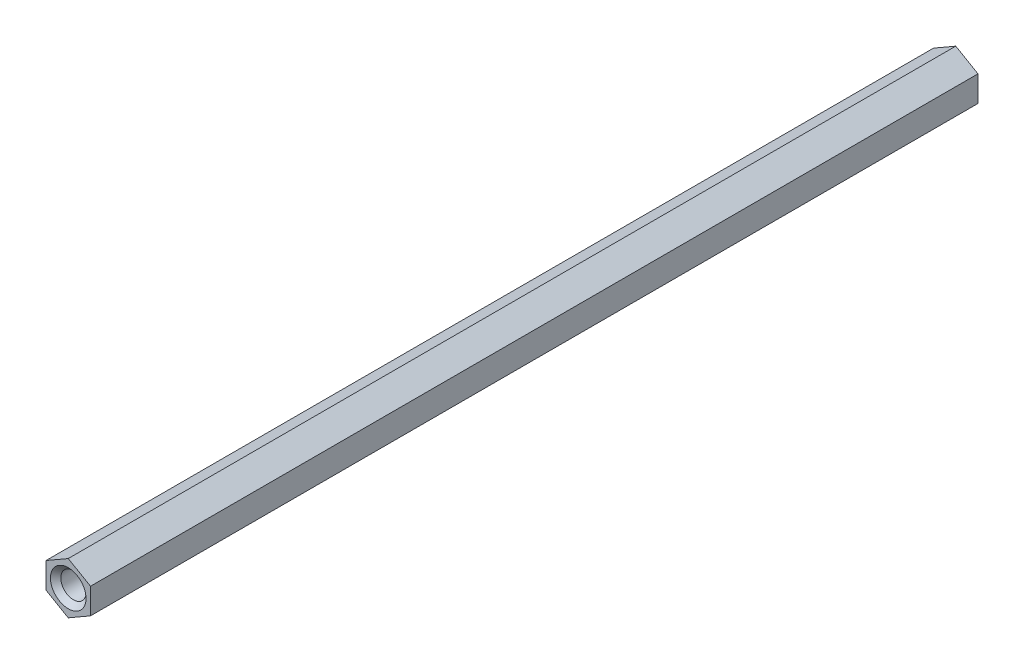
SolidWorks part; units mm, degrees
ref_plane "Front Plane" through (0, 0, 0) normal (0, 0, 1) x (1, 0, 0)
ref_plane "Top Plane" through (0, 0, 0) normal (0, 1, 0) x (1, 0, 0)
ref_plane "Right Plane" through (0, 0, 0) normal (1, 0, 0) x (0, 0, -1)
sketch "Sketch1" plane through (0, 0, 0) normal (0, 0, 1) x (1, 0, 0)
  line L0 (-4.7625, 0) -> (4.7625, 0) construction
  line L9 (0, 5.4993) -> (-4.7625, 2.7496) construction
  line L10 (-4.7625, 2.7496) -> (-4.7625, -2.7496) construction
  line L11 (-4.7625, -2.7496) -> (0, -5.4993) construction
  line L12 (0, -5.4993) -> (4.7625, -2.7496) construction
  line L13 (4.7625, -2.7496) -> (4.7625, 2.7496) construction
  line L14 (4.7625, 2.7496) -> (0, 5.4993) construction
  circle A3 centre (0, 0) radius 4.7625 construction
  point P4 (0, 0)
  dimension "Width" = 9.525
sketch "Sketch2" plane through (0, 0, 0) normal (1, 0, 0) x (0, 0, -1)
  line L0 (95, 5.4993) -> (-95, 5.4993) construction
  point P3 (-84.0463, 5.4993)
  point P4 (0, 5.4993)
  point P5 (84.0463, 5.4993)
  dimension "Length" = 190
  dimension "D1" = 10.9537
  dimension "D2" = 10.9537
sketch "Sketch3" plane through (0, 0, 0) normal (0, 0, 1) x (1, 0, 0)
  line L1 (0, 5.4993) -> (4.7625, 2.7496)
  line L2 (4.7625, 2.7496) -> (4.7625, -2.7496)
  line L3 (4.7625, -2.7496) -> (0, -5.4993)
  line L4 (0, -5.4993) -> (-4.7625, -2.7496)
  line L5 (-4.7625, -2.7496) -> (-4.7625, 2.7496)
  line L6 (-4.7625, 2.7496) -> (0, 5.4993)
extrude "Boss-Extrude1" add sketch "Sketch3" along normal mid plane 190
sketch "Sketch6" plane through (0, 0, 95) normal (0, 0, 1) x (1, 0, 0)
  point P0 (0, 0)
hole_wizard "1/4-28 Tapped Hole1" positions "Sketch6" profile "Sketch5" tap size "1/4-28" standard "ANSI Inch"
sketch "Sketch5" plane through (0, 0, 95) normal (1, 0, 0) x (0, -1, 0)
  line L0 (0, 0) -> (0, 16.8654)
  line L1 (0, 16.8654) -> (2.7051, 15.24)
  line L2 (2.7051, 15.24) -> (2.7051, 1.1049)
  line L3 (2.7051, 1.1049) -> (3.81, 0)
  line L5 (3.81, 0) -> (0, 0)
  line L6 (-2.7051, 1.1049) -> (-3.81, 0) construction
  line L10 (0, 16.8654) -> (-2.7051, 15.24) construction
  line L11 (0, -6.35) -> (0, 107.95) construction
  dimension "Tap Drill Dia." = 5.4102
  dimension "Tap Drill Depth" = 15.24
  dimension "Near C'Sink Dia." = 7.62
  dimension "Near C'Sink Angle" = 90
  dimension "Drill Angle" = 118
cosmetic thread "Hole Thread1" parameters "D1"=12.7, "D2"=6.35
sketch "Sketch9" plane through (0, 0, -95) normal (0, 0, -1) x (-1, 0, 0)
  point P0 (0, 0)
hole_wizard "1/4-28 Tapped Hole2" positions "Sketch9" profile "Sketch8" tap size "1/4-28" standard "ANSI Inch"
cosmetic thread "Hole Thread2" parameters "D1"=12.7, "D2"=6.35
sketch "Sketch8" plane through (0, 0, -95) normal (1, 0, 0) x (0, 1, 0)
  line L0 (0, 0) -> (0, 18.8593)
  line L1 (0, 18.8593) -> (2.7051, 17.2339)
  line L2 (2.7051, 17.2339) -> (2.7051, 1.1049)
  line L3 (2.7051, 1.1049) -> (3.81, 0)
  line L5 (3.81, 0) -> (0, 0)
  line L6 (-2.7051, 1.1049) -> (-3.81, 0) construction
  line L10 (0, 18.8593) -> (-2.7051, 17.2339) construction
  line L11 (0, -6.35) -> (0, 107.95) construction
  dimension "Tap Drill Dia." = 5.4102
  dimension "Tap Drill Depth" = 17.2339
  dimension "Near C'Sink Dia." = 7.62
  dimension "Near C'Sink Angle" = 90
  dimension "Drill Angle" = 118
equation "\"D1@Boss-Extrude1\" = \"Length@Sketch2\""
equation "\"D1@Sketch2\" = \"Width@Sketch1\" * 1.15"
equation "\"D2@Sketch2\"=\"D1@Sketch2\""
